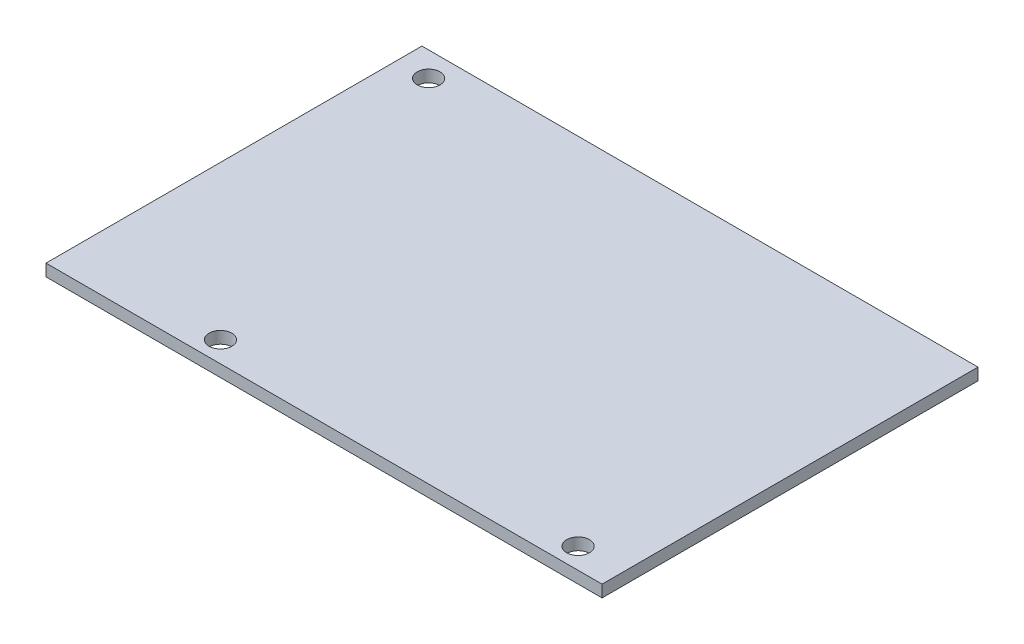
SolidWorks part; units mm, degrees
material "FR-4"
ref_plane "Front Plane" through (0, 0, 0) normal (0, 0, 1) x (1, 0, 0)
ref_plane "Top Plane" through (0, 0, 0) normal (0, 1, 0) x (1, 0, 0)
ref_plane "Right Plane" through (0, 0, 0) normal (1, 0, 0) x (0, 0, -1)
sketch "Sketch1" plane through (0, 0, 0) normal (0, 1, 0) x (1, 0, 0)
  line L1 (0, 0) -> (74.4, 0)
  line L2 (0, 0) -> (0, 50.3)
  line L3 (0, 50.3) -> (74.4, 50.3)
  line L4 (74.4, 0) -> (74.4, 50.3)
  dimension "D1" = 74.4
  dimension "D2" = 50.3
extrude "Boss-Extrude1" add sketch "Sketch1" along normal blind 1.6
sketch "Sketch2"
sketch "Sketch3" plane through (0, 1.6, 0) normal (0, 1, 0) x (1, 0, 0)
  line L0 (0, 50.3) -> (0, 0) construction
  line L1 (0, 0) -> (74.4, 0) construction
  line L2 (74.4, 50.3) -> (0, 50.3) construction
  circle A0 centre (20.5486, 2.794) radius 1.524
  circle A1 centre (68.4022, 2.794) radius 1.524
  circle A2 centre (4.191, 46.998) radius 1.524
  dimension "D1" = 3.048
  dimension "D2" = 3.048
  dimension "D7" = 3.048
  dimension "D3" = 20.5486
  dimension "D4" = 47.8536
  dimension "D5" = 2.794
  dimension "D6" = 2.794
  dimension "D8" = 3.302
  dimension "D9" = 4.191
extrude "Cut-Extrude1" cut sketch "Sketch3" against normal blind 1.6
